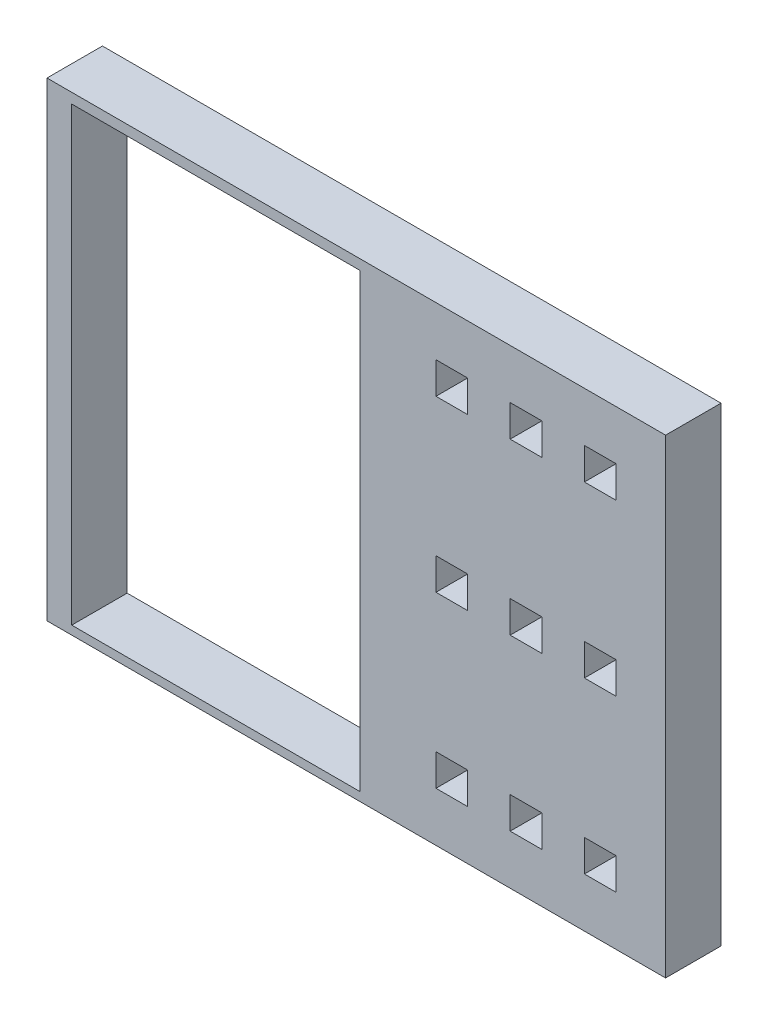
SolidWorks part; units mm, degrees
ref_plane "Alzado" through (0, 0, 0) normal (0, 0, 1) x (1, 0, 0)
ref_plane "Planta" through (0, 0, 0) normal (0, 1, 0) x (1, 0, 0)
ref_plane "Vista lateral" through (0, 0, 0) normal (1, 0, 0) x (0, 0, -1)
sketch "Croquis1" plane through (0, 0, 0) normal (0, 0, 1) x (1, 0, 0)
  line L0 (-73.8708, 38.9382) -> (51.1292, 38.9382)
  line L1 (51.1292, 38.9382) -> (51.1292, -56.0618)
  line L2 (51.1292, -56.0618) -> (-73.8708, -56.0618)
  line L3 (-73.8708, -56.0618) -> (-73.8708, 38.9382)
  dimension "D1" = 125
  dimension "D2" = 95
extrude "Saliente-Extruir1" add sketch "Croquis1" along normal blind 11.2 contours L3 L0 L1 L2
sketch "Croquis2" plane through (0, 0, 0) normal (0, 0, -1) x (-1, 0, 0)
  line L0 (73.8708, 38.9382) -> (73.8708, 36.8882) construction
  line L1 (73.8708, -56.0618) -> (73.8708, 38.9382) construction
  line L2 (73.8708, 36.8882) -> (68.8708, 36.8882) construction
  line L3 (68.8708, 36.8882) -> (68.8708, -54.3118)
  line L4 (68.8708, -54.3118) -> (10.5708, -54.3118)
  line L5 (10.5708, -54.3118) -> (10.5708, 36.8882)
  line L6 (10.5708, 36.8882) -> (68.8708, 36.8882)
  line L7 (73.8708, 38.9382) -> (-51.1292, 38.9382) construction
  line L10 (-51.1292, 38.9382) -> (-51.1292, 28.9382) construction
  line L11 (-51.1292, 38.9382) -> (-51.1292, -56.0618) construction
  line L12 (-51.1292, 28.9382) -> (-41.1292, 28.9382) construction
  line L13 (-41.1292, 28.9382) -> (-41.1292, 22.5382)
  line L14 (-41.1292, 22.5382) -> (-34.7292, 22.5382)
  line L15 (-34.7292, 22.5382) -> (-34.7292, 28.9382)
  line L16 (-34.7292, 28.9382) -> (-41.1292, 28.9382)
  line L47 (-41.0566, 38.9382) -> (-37.9292, 28.9382) construction
  line L48 (-19.7292, 28.9382) -> (-26.1292, 28.9382)
  line L49 (-26.1292, 28.9382) -> (-26.1292, 22.5382)
  line L50 (-26.1292, 22.5382) -> (-19.7292, 22.5382)
  line L51 (-19.7292, 22.5382) -> (-19.7292, 28.9382)
  line L52 (-4.7292, 28.9382) -> (-11.1292, 28.9382)
  line L53 (-11.1292, 28.9382) -> (-11.1292, 22.5382)
  line L54 (-11.1292, 22.5382) -> (-4.7292, 22.5382)
  line L55 (-4.7292, 22.5382) -> (-4.7292, 28.9382)
  line L56 (-19.7292, -5.3618) -> (-26.1292, -5.3618)
  line L57 (-26.1292, -5.3618) -> (-26.1292, -11.7618)
  line L58 (-26.1292, -11.7618) -> (-19.7292, -11.7618)
  line L59 (-19.7292, -11.7618) -> (-19.7292, -5.3618)
  line L60 (-4.7292, -5.3618) -> (-11.1292, -5.3618)
  line L61 (-11.1292, -5.3618) -> (-11.1292, -11.7618)
  line L62 (-11.1292, -11.7618) -> (-4.7292, -11.7618)
  line L63 (-4.7292, -11.7618) -> (-4.7292, -5.3618)
  line L64 (-19.7292, -39.6618) -> (-26.1292, -39.6618)
  line L65 (-26.1292, -39.6618) -> (-26.1292, -46.0618)
  line L66 (-26.1292, -46.0618) -> (-19.7292, -46.0618)
  line L67 (-19.7292, -46.0618) -> (-19.7292, -39.6618)
  line L68 (-4.7292, -39.6618) -> (-11.1292, -39.6618)
  line L69 (-11.1292, -39.6618) -> (-11.1292, -46.0618)
  line L70 (-11.1292, -46.0618) -> (-4.7292, -46.0618)
  line L71 (-4.7292, -46.0618) -> (-4.7292, -39.6618)
  line L72 (-34.7292, -5.3618) -> (-41.1292, -5.3618)
  line L73 (-41.1292, -5.3618) -> (-41.1292, -11.7618)
  line L74 (-41.1292, -11.7618) -> (-34.7292, -11.7618)
  line L75 (-34.7292, -11.7618) -> (-34.7292, -5.3618)
  line L76 (-34.7292, -39.6618) -> (-41.1292, -39.6618)
  line L77 (-41.1292, -39.6618) -> (-41.1292, -46.0618)
  line L78 (-41.1292, -46.0618) -> (-34.7292, -46.0618)
  line L79 (-34.7292, -46.0618) -> (-34.7292, -39.6618)
  line L80 (-4.7292, 28.9382) -> (-4.7292, 36.8882) construction
  line L81 (-4.7292, 36.8882) -> (10.5708, 36.8882) construction
  line L82 (-4.7292, -46.0618) -> (-4.7292, -54.3118) construction
  line L83 (-4.7292, -54.3118) -> (10.5708, -54.3118) construction
  line L84 (-51.1292, -56.0618) -> (73.8708, -56.0618) construction
  dimension "D1" = 5
  dimension "D2" = 91.2
  dimension "D3" = 10
  dimension "D4" = 10
  dimension "D5" = 6.4
  dimension "D6" = 6.4
  dimension "D9" = 8.25
  dimension "D10" = 1.75
  dimension "D11" = 58.3
  dimension "D7" = 3
  dimension "D8" = 3
extrude "Cortar-Extruir1" cut sketch "Croquis2" against normal blind 32.5
sketch "Croquis3" plane through (0, 0, 0) normal (0, 0, -1) x (-1, 0, 0)
  line L0 (-37.9292, 22.5382) -> (-39.4292, 22.5382) construction
  line L1 (-41.1292, 22.5382) -> (-34.7292, 22.5382) construction
  line L2 (-37.9292, 22.5382) -> (-36.4292, 22.5382) construction
  line L3 (-39.4292, 22.5382) -> (-39.4292, 17.5382)
  line L4 (-39.4292, 17.5382) -> (10.5708, 17.5382)
  line L5 (10.5708, 36.8882) -> (10.5708, -54.3118) construction
  line L6 (-36.4292, 22.5382) -> (-36.4292, 20.5382)
  line L7 (-22.9292, 22.5382) -> (-24.4292, 22.5382) construction
  line L8 (-26.1292, 22.5382) -> (-19.7292, 22.5382) construction
  line L9 (-22.9292, 22.5382) -> (-21.4292, 22.5382) construction
  line L10 (-36.4292, 20.5382) -> (-24.4292, 20.5382)
  line L11 (-24.4292, 20.5382) -> (-24.4292, 22.5382)
  line L12 (-21.4292, 22.5382) -> (-21.4292, 20.5382)
  line L13 (-7.9292, 22.5382) -> (-9.4292, 22.5382) construction
  line L14 (-11.1292, 22.5382) -> (-4.7292, 22.5382) construction
  line L15 (-9.4292, 22.5382) -> (-9.4292, 20.5382)
  line L16 (-21.4292, 20.5382) -> (-9.4292, 20.5382)
  line L17 (-7.9292, 22.5382) -> (-6.4292, 22.5382) construction
  line L18 (-6.4292, 22.5382) -> (-6.4292, 20.5382)
  line L19 (-6.4292, 20.5382) -> (10.5708, 20.5382)
  line L20 (10.5708, 20.5382) -> (10.5708, 17.5382)
  line L21 (-39.4292, 22.5382) -> (-36.4292, 22.5382)
  line L22 (-24.4292, 22.5382) -> (-21.4292, 22.5382)
  line L23 (-9.4292, 22.5382) -> (-6.4292, 22.5382)
  line L24 (-9.4292, -11.7618) -> (-6.4292, -11.7618)
  line L25 (-6.4292, -11.7618) -> (-6.4292, -13.7618)
  line L26 (-6.4292, -13.7618) -> (10.5708, -13.7618)
  line L27 (10.5708, -13.7618) -> (10.5708, -16.7618)
  line L28 (-39.4292, -16.7618) -> (10.5708, -16.7618)
  line L29 (-39.4292, -11.7618) -> (-39.4292, -16.7618)
  line L30 (-39.4292, -11.7618) -> (-36.4292, -11.7618)
  line L31 (-36.4292, -11.7618) -> (-36.4292, -13.7618)
  line L32 (-36.4292, -13.7618) -> (-24.4292, -13.7618)
  line L33 (-24.4292, -13.7618) -> (-24.4292, -11.7618)
  line L34 (-24.4292, -11.7618) -> (-21.4292, -11.7618)
  line L35 (-21.4292, -11.7618) -> (-21.4292, -13.7618)
  line L36 (-21.4292, -13.7618) -> (-9.4292, -13.7618)
  line L37 (-9.4292, -11.7618) -> (-9.4292, -13.7618)
  line L38 (-9.4292, -46.0618) -> (-6.4292, -46.0618)
  line L39 (-6.4292, -46.0618) -> (-6.4292, -48.0618)
  line L40 (-6.4292, -48.0618) -> (10.5708, -48.0618)
  line L41 (10.5708, -48.0618) -> (10.5708, -51.0618)
  line L42 (-39.4292, -51.0618) -> (10.5708, -51.0618)
  line L43 (-39.4292, -46.0618) -> (-39.4292, -51.0618)
  line L44 (-39.4292, -46.0618) -> (-36.4292, -46.0618)
  line L45 (-36.4292, -46.0618) -> (-36.4292, -48.0618)
  line L46 (-36.4292, -48.0618) -> (-24.4292, -48.0618)
  line L47 (-24.4292, -48.0618) -> (-24.4292, -46.0618)
  line L48 (-24.4292, -46.0618) -> (-21.4292, -46.0618)
  line L49 (-21.4292, -46.0618) -> (-21.4292, -48.0618)
  line L50 (-21.4292, -48.0618) -> (-9.4292, -48.0618)
  line L51 (-9.4292, -46.0618) -> (-9.4292, -48.0618)
  dimension "D1" = 3
extrude "Cortar-Extruir2" cut sketch "Croquis3" against normal blind 4
